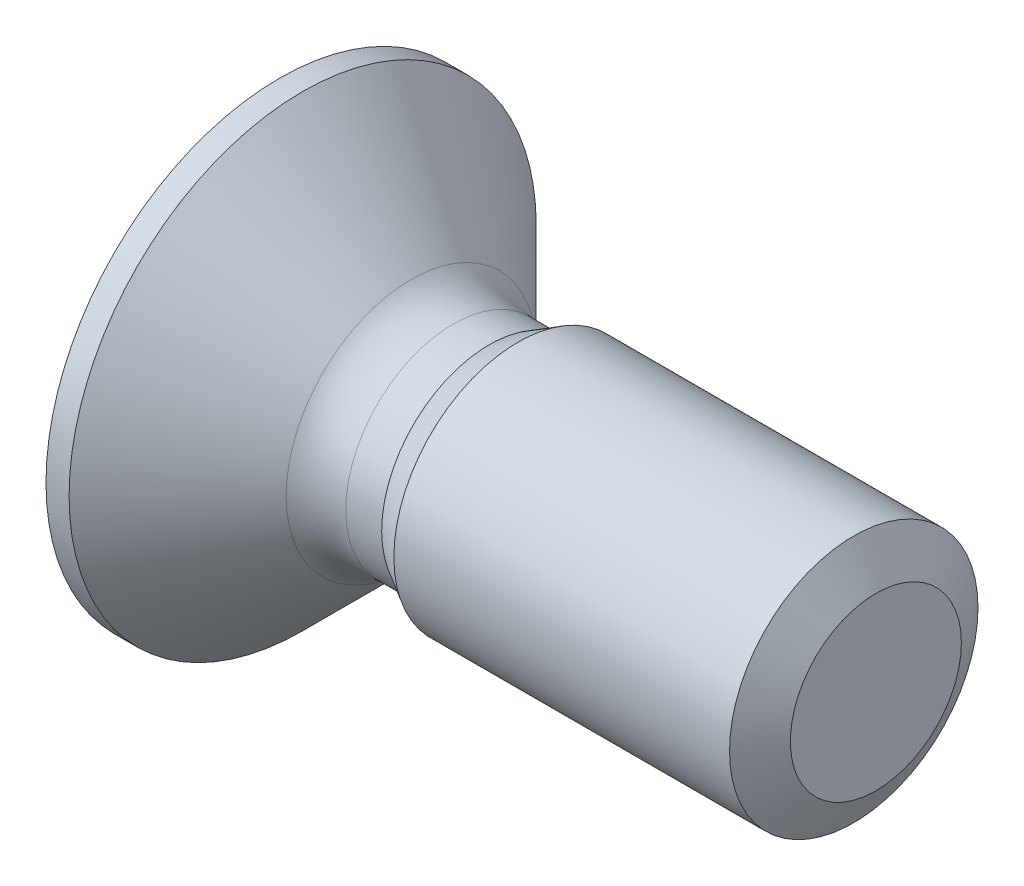
SolidWorks part; units mm, degrees
revolve "基体-旋转" add sketch "草图1" angle 360 about L0
sketch "草图1" plane through (0, 0, 0) normal (0, 0, 1) x (1, 0, 0)
  line L0 (0, 0) -> (4.4175, 0) construction
  line L1 (0, 0) -> (0, 2.35)
  line L2 (0, 2.35) -> (0.2325, 2.35)
  line L3 (0.2325, 2.35) -> (1.3243, 1.2582)
  line L4 (1.7485, 1.0825) -> (2.1099, 1.0825)
  line L5 (2.1099, 1.0825) -> (2.4, 1.25)
  line L6 (2.4, 1.25) -> (6, 1.25)
  line L7 (6, 1.25) -> (6, 0)
  line L8 (0, 0) -> (6, 0)
  arc A0 (1.7485, 1.0825) -> (1.3243, 1.2582) centre (1.7485, 1.6825) cw
  point P12 (1.5, 1.0825)
  dimension "D2" = 0.6
  dimension "D1" = 2.165
  dimension "d" = 2.5
  dimension "dk" = 4.7
  dimension "k" = 1.5
  dimension "D5" = 45
  dimension "a" = 0.9
  dimension "l" = 6
  dimension "D8" = 30
cosmetic thread "装饰螺纹线2" parameters "D1"=3.6, "D2"=2.05
material "4.8级"
ref_plane "前视" through (0, 0, 0) normal (0, 0, 1) x (1, 0, 0)
ref_plane "上视" through (0, 0, 0) normal (0, 1, 0) x (1, 0, 0)
ref_plane "右视" through (0, 0, 0) normal (1, 0, 0) x (0, 0, -1)
sketch "尺寸草图" plane through (0, 0, 0) normal (0, 0, 1) x (1, 0, 0)
  line L0 (0, 0) -> (6, 0)
  point P3 (1.5, 0)
  point P4 (0.9, 0)
  point P5 (2.5, 0)
  point P6 (4.7, 0)
  point P7 (3.1, 0)
  point P8 (3.5943, 0)
  point P9 (5.4, 0)
  point P10 (4.2, 0)
  point P11 (5.55, 0)
  dimension "d" = 2.5
  dimension "dk" = 4.7
  dimension "k" = 1.5
  dimension "a" = 0.9
  dimension "l" = 6
  dimension "r" = 0.6
  dimension "m" = 2.9
  dimension "h" = 1.8
  dimension "p" = 0.45
sketch "草图2" plane through (0, 0, 0) normal (0, 0, 1) x (1, 0, 0)
  line L0 (5.7774, 1.25) -> (6.2274, 1.25)
  line L1 (6.2274, 1.25) -> (6, 0.8603)
  line L2 (6, 0.8603) -> (5.7774, 1.25)
  line L3 (6, -1.25) -> (6, 1.25) construction
  line L6 (0, 0) -> (-0.4315, 0) construction
  dimension "D1" = 0.45
  dimension "D2" = 0.3897
  dimension "D3" = 1.25
  dimension "D4" = 60
revolve "切除-旋转1" cut sketch "草图2" angle 360 about L6
pattern_linear "阵列(线性)1" [suppressed] count 8 spacing 0.45 along (1, 0, 0)
sketch "草图3" plane through (0, 0, 0) normal (-1, 0, 0) x (0, 0, 1)
  line L0 (0, 0) -> (1.6329, 0) construction
  line L1 (0, 0) -> (0, 0.8499) construction
  line L2 (-1.45, 0.225) -> (1.45, 0.225)
  line L3 (-1.45, 0.225) -> (-1.45, -0.225)
  line L4 (-1.45, -0.225) -> (1.45, -0.225)
  line L5 (1.45, 0.225) -> (1.45, -0.225)
  dimension "m" = 2.9
  dimension "D1" = 0.45
ref_plane "基准面1" through (1.8, 0, 0) normal (-1, 0, 0) x (0, 0, 1)
sketch "草图4" plane through (1.8, 0, 0) normal (-1, 0, 0) x (0, 0, 1)
  point P0 (0, 0)
loft "切除-放样1" cut profiles "草图3", "草图4"
pattern_circular "阵列(圆周)1" count 2 every 90 about axis through (0, 0, 0) along (1, 0, 0) of "切除-放样1"
equation "\"l@草图1\" = \"l@尺寸草图\""
equation "\"k@草图1\" = \"k@尺寸草图\""
equation "\"a@草图1\" = \"a@尺寸草图\""
equation "\"d@草图1\" = \"d@尺寸草图\""
equation "\"dk@草图1\" = \"dk@尺寸草图\""
equation "\"D2@草图1\" = \"r@尺寸草图\""
equation "\"m@草图3\" = \"m@尺寸草图\""
equation "\"h@基准面1\" = \"h@尺寸草图\""
equation "\"D3@阵列(线性)1\" = \"p@尺寸草图\""
equation "\"D3@草图2\" = \"d@草图1\" / 2"
equation "\"D1@装饰螺纹线2\" = \"l@草图1\" - \"k@草图1\" - \"a@草图1\""
equation "\"D2@装饰螺纹线2\" = \"d@尺寸草图\"- \"p@尺寸草图\""
equation "\"D1@阵列(线性)1\" = (  \"l@草图1\" - \"k@草图1\" - \"a@草图1\" )  / \"p@尺寸草图\""
equation "\"D1@草图3\" = \"p@尺寸草图\""
equation "\"D1@草图1\" = \"d@尺寸草图\"*0.866"
equation "\"D2@草图2\" = \"p@尺寸草图\"*0.866"
equation "\"D1@草图2\" = \"p@尺寸草图\""
